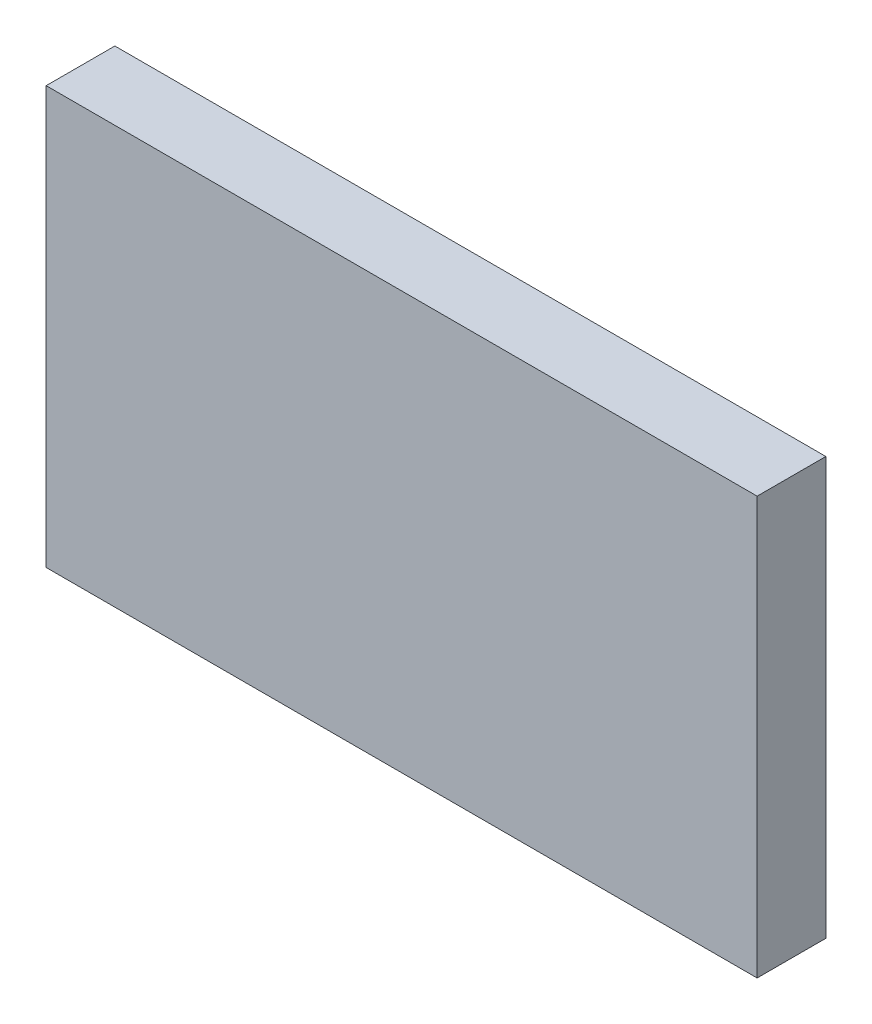
SolidWorks part; units mm, degrees
ref_plane "Front Plane" through (0, 0, 0) normal (0, 0, 1) x (1, 0, 0)
ref_plane "Top Plane" through (0, 0, 0) normal (0, 1, 0) x (1, 0, 0)
ref_plane "Right Plane" through (0, 0, 0) normal (1, 0, 0) x (0, 0, -1)
sketch "Sketch1" plane through (0, 0, 0) normal (0, 0, 1) x (1, 0, 0)
  line L1 (-20.7, 12.15) -> (20.7, 12.15)
  line L2 (-20.7, 12.15) -> (-20.7, -12.15)
  line L3 (-20.7, -12.15) -> (20.7, -12.15)
  line L4 (20.7, 12.15) -> (20.7, -12.15)
  line L5 (-20.7, 12.15) -> (20.7, -12.15) construction
  line L6 (-20.7, -12.15) -> (20.7, 12.15) construction
  point P0 (0, 0)
  dimension "D1" = 41.4
  dimension "D2" = 24.3
extrude "Boss-Extrude1" add sketch "Sketch1" against normal blind 4
sketch "Sketch2" plane through (0, 0, -4) normal (0, 0, -1) x (-1, 0, 0)
  line L0 (20.7, -12.15) -> (-20.7, -12.15) construction
  line L1 (12, -11.7) -> (-12, -11.7)
  line L2 (12, -11.7) -> (12, -11.4)
  line L3 (12, -11.4) -> (-12, -11.4)
  line L4 (-12, -11.7) -> (-12, -11.4)
  line L5 (12, -11.7) -> (-12, -11.4) construction
  line L6 (12, -11.4) -> (-12, -11.7) construction
  point P0 (0, -11.55)
  point P7 (0, 0)
  dimension "D1" = 0.3
  dimension "D2" = 0.75
  dimension "D3" = 24
extrude "Boss-Extrude2" add sketch "Sketch2" along normal blind 3
